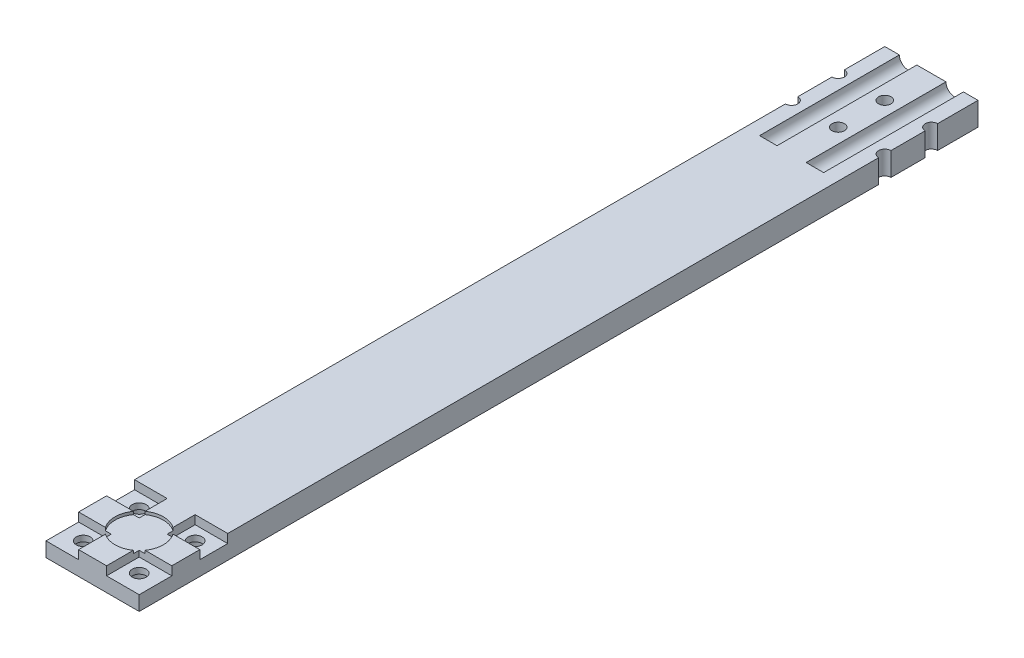
SolidWorks part; units mm, degrees
material "Copper"
ref_plane "Front Plane" through (0, 0, 0) normal (0, 0, 1) x (1, 0, 0)
ref_plane "Top Plane" through (0, 0, 0) normal (0, 1, 0) x (1, 0, 0)
ref_plane "Right Plane" through (0, 0, 0) normal (1, 0, 0) x (0, 0, -1)
sketch "Sketch1" plane through (0, 0, 0) normal (0, 1, 0) x (1, 0, 0)
  line L1 (-25.4, 228.6) -> (25.4, 228.6)
  line L2 (-25.4, 228.6) -> (-25.4, -228.6)
  line L3 (-25.4, -228.6) -> (25.4, -228.6)
  line L4 (25.4, 228.6) -> (25.4, -228.6)
  dimension "D1" = 457.2
  dimension "D2" = 50.8
  dimension "D3" = 25.4
  dimension "D4" = 228.6
extrude "Boss-Extrude1" add sketch "Sketch1" along normal blind 12.7
sketch "Sketch2" plane through (0, 0, -228.6) normal (0, 0, -1) x (-1, 0, 0)
  line L0 (-25.4, 12.7) -> (25.4, 12.7) construction
  line L1 (-25.4, 0) -> (25.4, 0) construction
  line L2 (25.4, 12.7) -> (-25.4, 12.7) construction
  circle A0 centre (-12.7, 12.7) radius 4.7625
  circle A1 centre (12.7, 12.7) radius 4.7625
  circle A2 centre (-12.7, 0) radius 4.7625
  circle A3 centre (12.7, 0) radius 4.7625
  point P12 (0, 12.7)
  point P15 (0, 12.7)
  dimension "D1" = 9.525
  dimension "D2" = 12.7
  dimension "D3" = 12.7
extrude "Cut-Extrude1" cut sketch "Sketch2" against normal blind 76.2
hole_wizard "1/4 Clearance Hole1" positions "Sketch4" profile "Sketch3" hole size "1/4" standard "ANSI Inch" end condition through all
sketch "Sketch4" plane through (0, 12.7, 0) normal (0, 1, 0) x (1, 0, 0)
  line L0 (25.4, -228.6) -> (25.4, 228.6) construction
  line L1 (-25.4, 228.6) -> (-25.4, -228.6) construction
  point P0 (0, 203.2)
  point P2 (0, 177.8)
  point P4 (25.4, 203.2)
  point P8 (25.4, 177.8)
  point P10 (-25.4, 177.8)
  point P14 (-25.4, 203.2)
sketch "Sketch3" plane through (0, 12.7, -203.2) normal (1, 0, 0) x (0, 0, 1)
  line L0 (0, 0) -> (0, 12.7)
  line L1 (0, 12.7) -> (3.3782, 12.7)
  line L2 (3.3782, 12.7) -> (3.3782, 0)
  line L5 (3.3782, 0) -> (0, 0)
  line L11 (0, -6.35) -> (0, 107.95) construction
  dimension "Thru Hole Dia." = 6.7564
  dimension "Thru Hole Depth" = 12.7
sketch "Sketch11" plane through (0, 12.7, 0) normal (0, 1, 0) x (1, 0, 0)
  line L0 (-25.4, -228.6) -> (25.4, -228.6) construction
  line L1 (-25.4, 174.4218) -> (-25.4, -228.6) construction
  circle A0 centre (0, -203.2) radius 13.208
  dimension "D1" = 26.416
  dimension "D2" = 25.4
  dimension "D3" = 25.4
extrude "Cut-Extrude2" cut sketch "Sketch11" against normal blind 1.5875
sketch "Sketch13" plane through (0, 12.7, 0) normal (0, 1, 0) x (1, 0, 0)
  line L0 (-25.4, 174.4218) -> (-25.4, -228.6) construction
  line L1 (-25.4, -228.6) -> (25.4, -228.6) construction
  circle A0 centre (-15.24, -187.96) radius 3.81
  circle A1 centre (15.24, -187.96) radius 3.81
  circle A2 centre (15.24, -218.44) radius 3.81
  circle A3 centre (-15.24, -218.44) radius 3.81
  dimension "D1" = 7.62
  dimension "D2" = 30.48
  dimension "D3" = 30.48
  dimension "D4" = 10.16
  dimension "D5" = 10.16
extrude "Cut-Extrude3" cut sketch "Sketch13" against normal through all
sketch "Sketch15" plane through (0, 12.7, 0) normal (0, 1, 0) x (1, 0, 0)
  line L0 (-25.4, 174.4218) -> (-25.4, -228.6) construction
  line L1 (-7.62, -180.34) -> (-25.4, -180.34)
  line L2 (-7.62, -180.34) -> (-7.62, -195.58)
  line L3 (-7.62, -195.58) -> (-25.4, -195.58)
  line L4 (-25.4, -180.34) -> (-25.4, -195.58)
  line L5 (25.4, -228.6) -> (25.4, 174.4218) construction
  line L6 (25.4, -180.34) -> (7.62, -180.34)
  line L7 (25.4, -180.34) -> (25.4, -195.58)
  line L8 (25.4, -195.58) -> (7.62, -195.58)
  line L9 (7.62, -180.34) -> (7.62, -195.58)
  line L10 (-25.4, -228.6) -> (25.4, -228.6) construction
  line L11 (-25.4, -210.82) -> (-7.62, -210.82)
  line L12 (-25.4, -210.82) -> (-25.4, -228.6)
  line L13 (-25.4, -228.6) -> (-7.62, -228.6)
  line L14 (-7.62, -210.82) -> (-7.62, -228.6)
  line L16 (25.4, -210.82) -> (7.62, -210.82)
  line L17 (25.4, -210.82) -> (25.4, -228.6)
  line L18 (25.4, -228.6) -> (7.62, -228.6)
  line L19 (7.62, -210.82) -> (7.62, -228.6)
  circle A1 centre (-15.24, -187.96) radius 3.81 construction
  circle A2 centre (-15.24, -218.44) radius 3.81 construction
  dimension "D1" = 7.62
  dimension "D2" = 7.62
  dimension "D3" = 7.62
  dimension "D4" = 7.62
extrude "Cut-Extrude4" cut sketch "Sketch15" against normal blind 4.7625
sketch "Sketch16" plane through (0, 0, 0) normal (0, -1, 0) x (1, 0, 0)
  circle A0 centre (-15.24, 218.44) radius 6.858
  circle A1 centre (15.24, 218.44) radius 6.858
  circle A2 centre (15.24, 187.96) radius 6.858
  circle A3 centre (-15.24, 187.96) radius 6.858
  dimension "D1" = 13.716
extrude "Cut-Extrude5" cut sketch "Sketch16" against normal blind 4.7625
